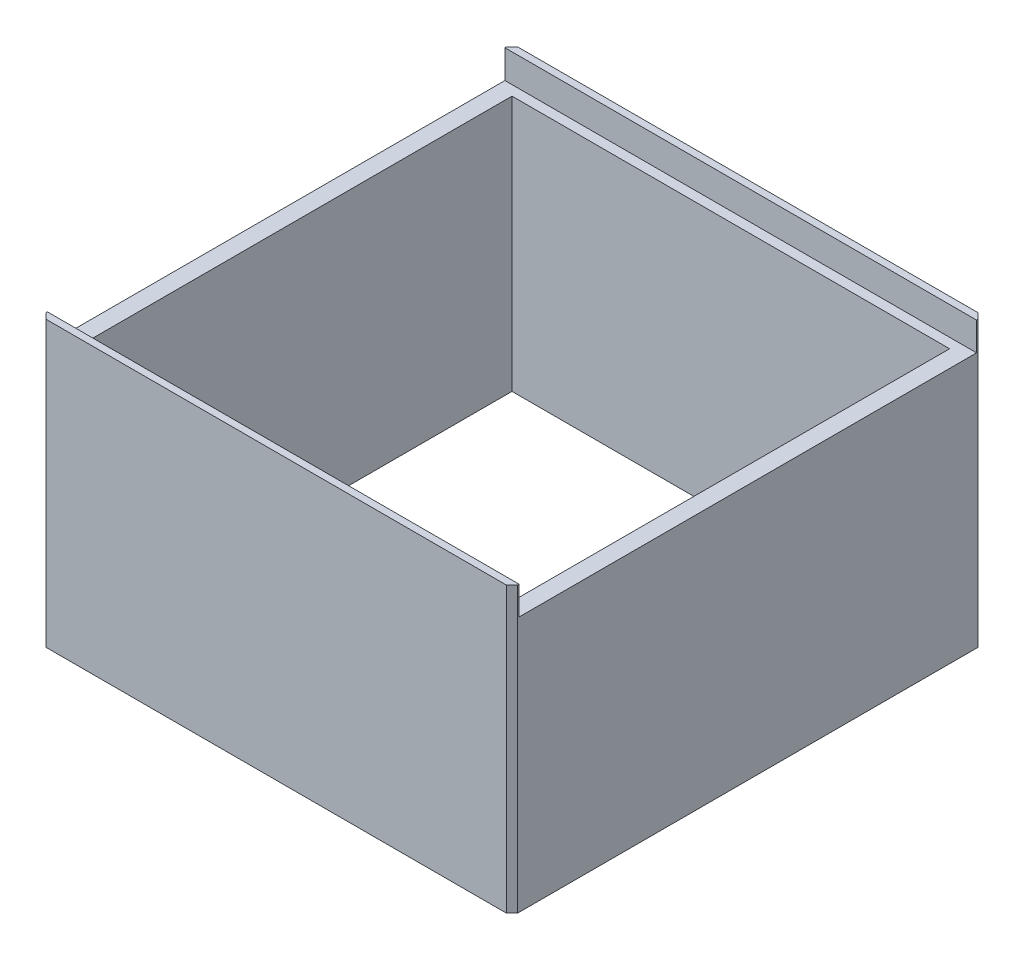
SolidWorks part; units mm, degrees
ref_plane "前视基准面" through (0, 0, 0) normal (0, 0, 1) x (1, 0, 0)
ref_plane "上视基准面" through (0, 0, 0) normal (0, 1, 0) x (1, 0, 0)
ref_plane "右视基准面" through (0, 0, 0) normal (1, 0, 0) x (0, 0, -1)
other "Configuration Table"
sketch "Sketch1" plane through (0, 0, 0) normal (0, 1, 0) x (1, 0, 0)
  line L1 (-40, 40) -> (40, 40)
  line L2 (-40, 40) -> (-40, -40)
  line L3 (-40, -40) -> (40, -40)
  line L4 (40, 40) -> (40, -40)
  line L5 (-40, 40) -> (40, -40) construction
  line L6 (-40, -40) -> (40, 40) construction
  line L7 (-41.5, 41.5) -> (41.5, 41.5)
  line L8 (-41.5, 41.5) -> (-41.5, -41.5)
  line L9 (-41.5, -41.5) -> (41.5, -41.5)
  line L10 (41.5, 41.5) -> (41.5, -41.5)
  line L11 (-41.5, 41.5) -> (41.5, -41.5) construction
  line L12 (-41.5, -41.5) -> (41.5, 41.5) construction
  line L13 (-38.5, 38.5) -> (38.5, 38.5)
  line L14 (-38.5, 38.5) -> (-38.5, -38.5)
  line L15 (-38.5, -38.5) -> (38.5, -38.5)
  line L16 (38.5, 38.5) -> (38.5, -38.5)
  line L17 (-38.5, 38.5) -> (38.5, -38.5) construction
  line L18 (-38.5, -38.5) -> (38.5, 38.5) construction
  point P0 (0, 0)
  point P6 (0, 0)
  point P11 (0, 0)
  dimension "D1" = 80
  dimension "D2" = 80
  dimension "D3" = 1.5
  dimension "D4" = 1.5
  dimension "D5" = 3
  dimension "D6" = 3
extrude "Boss-Extrude1" add sketch "Sketch1" along normal blind 50 contours L7 L10 L9 L8 | L13 L16 L15 L14
sketch "Sketch2" plane through (0, 50, 0) normal (0, 1, 0) x (1, 0, 0)
  line L1 (-50.25, 40.25) -> (50.25, 40.25)
  line L2 (-50.25, 40.25) -> (-50.25, -40.25)
  line L3 (-50.25, -40.25) -> (50.25, -40.25)
  line L4 (50.25, 40.25) -> (50.25, -40.25)
  line L5 (-50.25, 40.25) -> (50.25, -40.25) construction
  line L6 (-50.25, -40.25) -> (50.25, 40.25) construction
  point P0 (0, 0)
  dimension "D1" = 100.5
  dimension "D2" = 80.5
extrude "Cut-Extrude1" cut sketch "Sketch2" against normal blind 5
chamfer "Chamfer1" distance 1 angle 45 4 edges at (41.5, 25, -41.5) (41.5, 25, 41.5) (-41.5, 25, 41.5) (-41.5, 25, -41.5)
ref_plane "Plane1" through (0, 1, 0) normal (0, -1, 0) x (-1, 0, 0)
sketch "Sketch3" plane through (0, 1, 0) normal (0, -1, 0) x (-1, 0, 0)
  line L1 (-38.5, 38.5) -> (-30.5, 38.5)
  line L2 (-38.5, 38.5) -> (-38.5, 30.5)
  line L3 (-38.5, 30.5) -> (-30.5, 30.5)
  line L4 (-30.5, 38.5) -> (-30.5, 30.5)
  dimension "D1" = 8
  dimension "D2" = 8
extrude "Boss-Extrude2" add sketch "Sketch3" against normal blind 3
